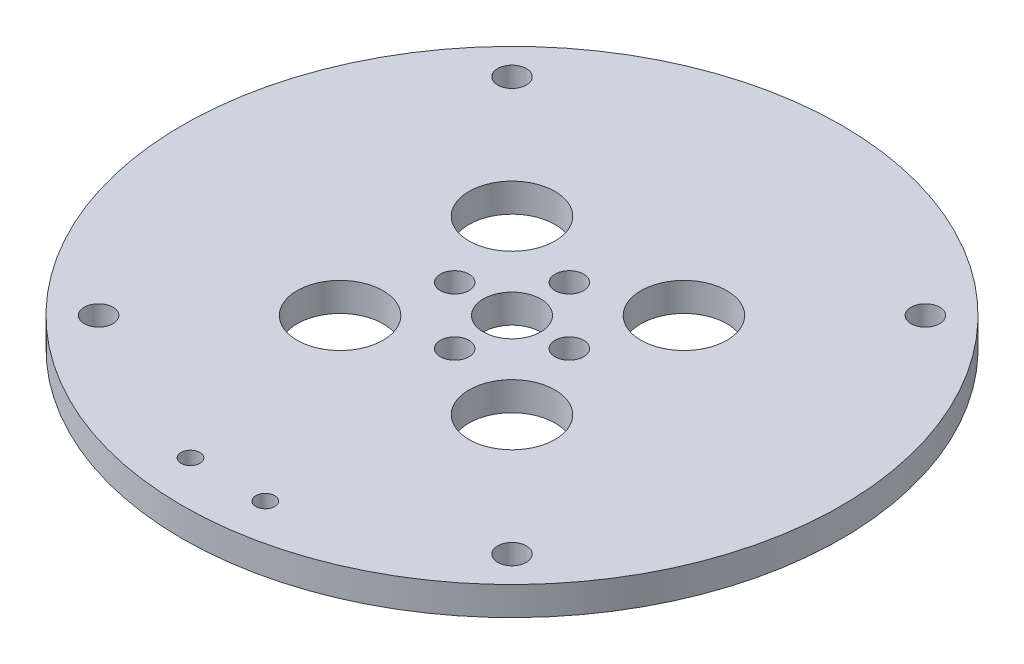
SolidWorks part; units mm, degrees
material "5052-H34"
ref_plane "正面" through (0, 0, 0) normal (0, 0, 1) x (1, 0, 0)
ref_plane "平面" through (0, 0, 0) normal (0, 1, 0) x (1, 0, 0)
ref_plane "右側面" through (0, 0, 0) normal (1, 0, 0) x (0, 0, -1)
sketch "ｽｹｯﾁ1" plane through (0, 0, 0) normal (0, 1, 0) x (1, 0, 0)
  line L0 (0, 57.5) -> (0, 0) construction
  line L1 (0, 0) -> (57.5, 0) construction
  line L2 (-6.5263, -49.5722) -> (0, 0) construction
  line L3 (0, 0) -> (0, -50) construction
  line L5 (36.0624, 36.0624) -> (-36.0624, 36.0624) construction
  line L6 (36.0624, 36.0624) -> (36.0624, -36.0624) construction
  line L7 (36.0624, -36.0624) -> (-36.0624, -36.0624) construction
  line L8 (-36.0624, 36.0624) -> (-36.0624, -36.0624) construction
  line L9 (36.0624, 36.0624) -> (-36.0624, -36.0624) construction
  line L10 (36.0624, -36.0624) -> (-36.0624, 36.0624) construction
  circle A0 centre (0, 0) radius 57.5
  circle A5 centre (0, 0) radius 44.5 construction
  circle A6 centre (10, 0) radius 2.5
  circle A10 centre (0, 0) radius 5
  circle A11 centre (0, -10) radius 2.5
  circle A12 centre (-10, 0) radius 2.5
  circle A13 centre (0, 10) radius 2.5
  circle A14 centre (0, 0) radius 10 construction
  circle A19 centre (15, 15) radius 7.5
  circle A20 centre (15, -15) radius 7.5
  circle A21 centre (-15, -15) radius 7.5
  circle A22 centre (-15, 15) radius 7.5
  circle A23 centre (0, 0) radius 15 construction
  circle A24 centre (0, 0) radius 50 construction
  circle A25 centre (-6.5263, -49.5722) radius 1.65
  circle A26 centre (6.5263, -49.5722) radius 1.65
  circle A27 centre (-36.0624, 36.0624) radius 2.5
  circle A28 centre (36.0624, 36.0624) radius 2.5
  circle A29 centre (36.0624, -36.0624) radius 2.5
  circle A30 centre (-36.0624, -36.0624) radius 2.5
  point P25 (0, 0)
  point P53 (0, 0)
  dimension "D1" = 115
  dimension "D2" = 102
  dimension "D3" = 5
  dimension "D4" = 4
  dimension "D5" = 89
  dimension "D6" = 5
  dimension "D7" = 10
  dimension "D8" = 20
  dimension "D9" = 4
  dimension "D11" = 15
  dimension "D12" = 30
  dimension "D13" = 30
  dimension "D14" = 30
  dimension "D15" = 100
  dimension "D16" = 3.3
  dimension "D17" = 7.5
extrude "ﾎﾞｽ - 押し出し1" add sketch "ｽｹｯﾁ1" along normal blind 5
